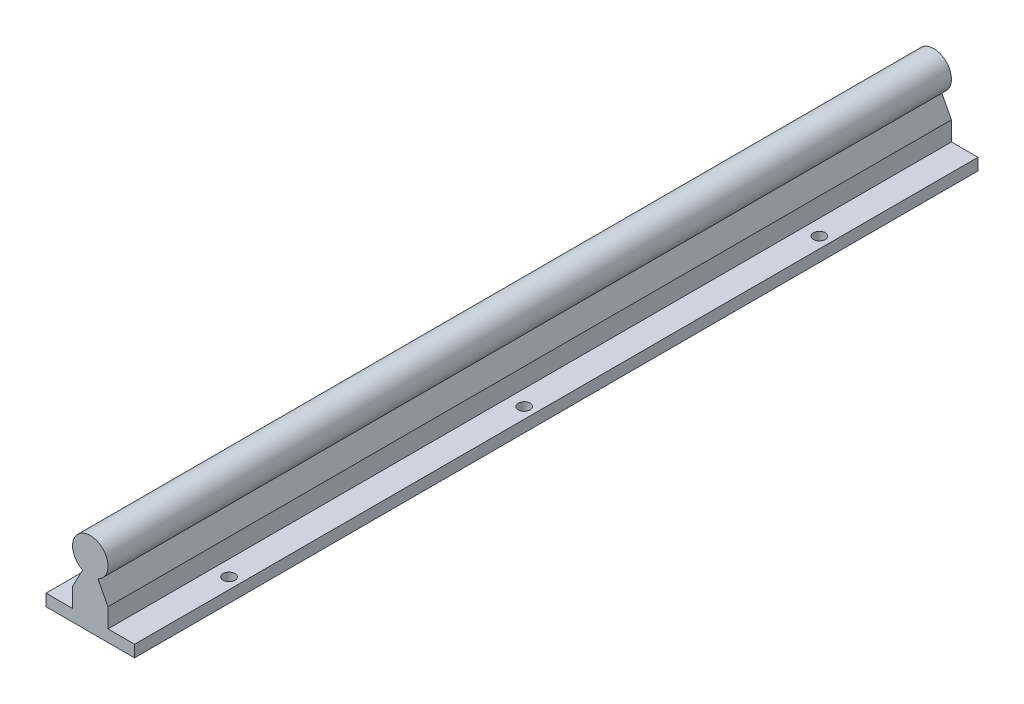
SolidWorks part; units mm, degrees
material "Chrome Stainless Steel"
ref_plane "Front Plane" through (0, 0, 0) normal (0, 0, 1) x (1, 0, 0)
ref_plane "Top Plane" through (0, 0, 0) normal (0, 1, 0) x (1, 0, 0)
ref_plane "Right Plane" through (0, 0, 0) normal (1, 0, 0) x (0, 0, -1)
sketch "Sketch1" plane through (0, 0, 0) normal (0, 0, 1) x (1, 0, 0)
  line L0 (19.7075, 0) -> (-10.2925, 0)
  line L1 (19.7075, 0) -> (19.7075, 4)
  line L2 (19.7075, 4) -> (10.7075, 4)
  line L3 (10.7075, 4) -> (10.7075, 10.5)
  line L4 (7.3075, 17) -> (10.7075, 10.5)
  line L5 (-1.2925, 10.5) -> (2.1075, 17)
  line L6 (4.7075, 2) -> (4.7075, 38.0795) construction
  line L9 (-1.2925, 4) -> (-1.2925, 10.5)
  line L10 (-10.2925, 0) -> (-10.2925, 4)
  line L11 (-10.2925, 4) -> (-1.2925, 4)
  arc A0 (7.3075, 17) -> (2.1075, 17) centre (4.7075, 22.4074) ccw
  point P17 (4.7075, 0)
  dimension "D5" = 6
  dimension "D1" = 15
  dimension "D2" = 4
  dimension "D4" = 17
  dimension "D6" = 2.6
  dimension "D8" = 22.4074
  dimension "D9" = 6
extrude "Boss-Extrude1" add sketch "Sketch1" along normal blind 285.75
sketch "Sketch2" plane through (0, 4, 0) normal (0, 1, 0) x (1, 0, 0)
  line L0 (-10.2925, -285.75) -> (-10.2925, 0) construction
  line L1 (-1.2925, 0) -> (-10.2925, 0) construction
  line L2 (19.7075, -285.75) -> (19.7075, 0) construction
  circle A0 centre (-6.5425, -50) radius 2
  circle A1 centre (15.9575, -50) radius 2
  circle A2 centre (15.9575, -150) radius 2
  circle A3 centre (-6.5425, -150) radius 2
  circle A4 centre (15.9575, -250) radius 2
  circle A5 centre (-6.5425, -250) radius 2
  dimension "D1" = 3.75
  dimension "D2" = 50
  dimension "D3" = 3.75
  dimension "D4" = 3
extrude "Cut-Extrude1" cut sketch "Sketch2" against normal up to next
